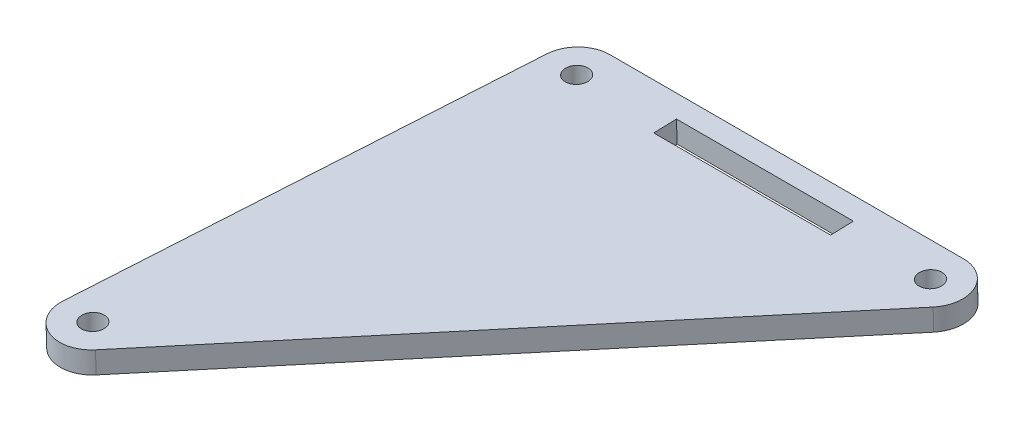
SolidWorks part; units mm, degrees
ref_plane "Front Plane" through (0, 0, 0) normal (0, 0, 1) x (1, 0, 0)
ref_plane "Top Plane" through (0, 0, 0) normal (0, 1, 0) x (1, 0, 0)
ref_plane "Right Plane" through (0, 0, 0) normal (1, 0, 0) x (0, 0, -1)
sketch "Sketch1" plane through (0, 345.4414, 10.7258) normal (0, 0.9995, 0.031) x (1, 0, 0)
  line L0 (-170.7266, 560.3385) -> (-272.3266, 560.3385)
  line L1 (-281.8097, 551.7059) -> (-293.7611, 424.7059)
  line L2 (-277.1773, 417.4647) -> (-163.6259, 544.4647)
  circle A0 centre (-284.278, 423.8135) radius 3.2639 construction
  circle A1 centre (-272.3266, 550.8135) radius 3.2639 construction
  circle A2 centre (-170.7266, 550.8135) radius 3.2639 construction
  circle A3 centre (-284.278, 423.8135) radius 3.2639
  circle A4 centre (-272.3266, 550.8135) radius 3.2639
  circle A5 centre (-170.7266, 550.8135) radius 3.2639
  arc A6 (-272.3266, 560.3385) -> (-281.8097, 551.7059) centre (-272.3266, 550.8135) ccw
  arc A7 (-293.7611, 424.7059) -> (-277.1773, 417.4647) centre (-284.278, 423.8135) ccw
  arc A8 (-163.6259, 544.4647) -> (-170.7266, 560.3385) centre (-170.7266, 550.8135) ccw
  point P11 (-285, 422.1845)
  point P16 (-271.3065, 550.8135)
  point P18 (-170.7266, 550.5473)
  point P19 (0, 0)
  point P20 (-277.2392, 417.52)
  point P21 (-285, 423.8135)
  dimension "D1" = 9.525
extrude "Boss-Extrude1" add sketch "Sketch1" along normal blind 6.35
sketch "Sketch2" plane through (0, 351.7883, 10.9228) normal (0, 0.9995, 0.031) x (1, 0, 0)
  line L1 (-246.9266, 554.0774) -> (-196.1266, 554.0774)
  line L2 (-246.9266, 554.0774) -> (-246.9266, 547.5496)
  line L3 (-246.9266, 547.5496) -> (-196.1266, 547.5496)
  line L4 (-196.1266, 554.0774) -> (-196.1266, 547.5496)
  circle A0 centre (-272.3266, 550.8135) radius 3.2639 construction
  circle A1 centre (-170.7266, 550.8135) radius 3.2639 construction
  dimension "D1" = 25.4
  dimension "D2" = 25.4
extrude "Cut-Extrude1" cut sketch "Sketch2" against normal through all
